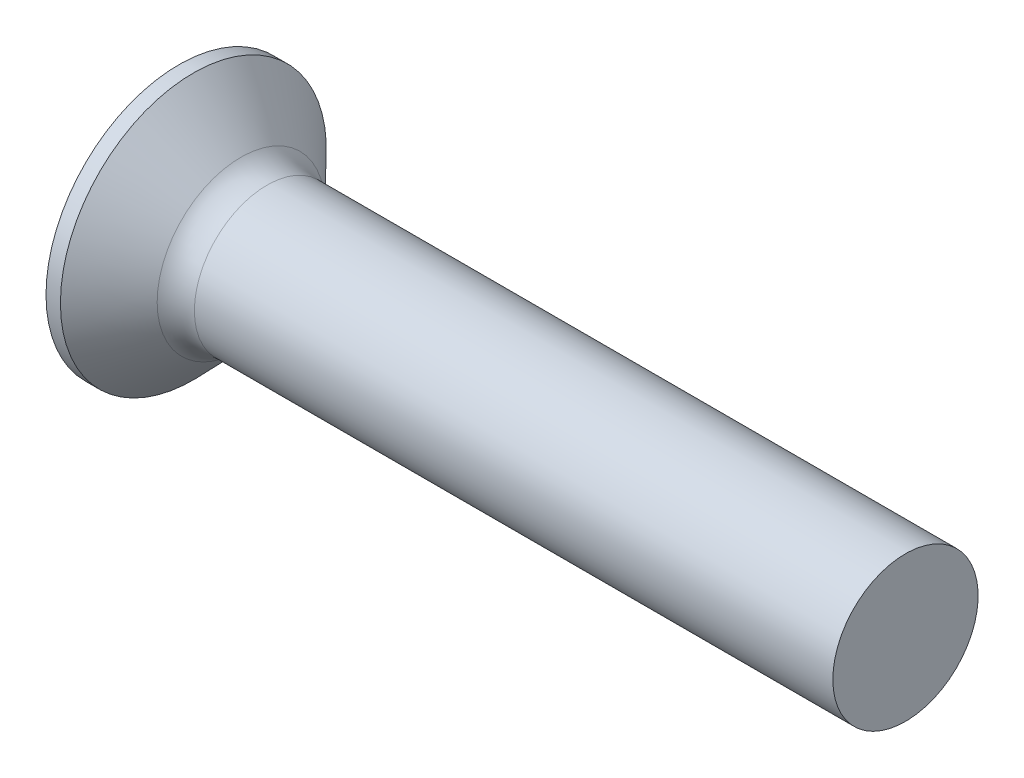
SolidWorks part; units mm, degrees
revolve "Base-Revolve" add sketch "BodySke" angle 360 about L5
sketch "BodySke" plane through (0, 0, 0) normal (0, 0, 1) x (1, 0, 0)
  line L0 (0, 0) -> (0, 9.15)
  line L1 (0, 9.15) -> (0.9924, 9.15)
  line L2 (5, 5) -> (50, 5)
  line L3 (50, 5) -> (50, 0)
  line L4 (50, 0) -> (0, 0)
  line L5 (-6.35, 0) -> (82.55, 0) construction
  line L6 (5, -5) -> (50, -5) construction
  line L7 (0.9924, -9.15) -> (5, -5) construction
  line L8 (0.9924, 9.15) -> (5, 5)
  line L9 (0, -9.15) -> (0.9924, -9.15) construction
  line L10 (6.5, 6.5875) -> (6.5, -2.9375) construction
  line L11 (0, 6.35) -> (0, -3.175) construction
  dimension "Length" = 50
  dimension "Thread_nom" = 50
cosmetic thread "ThreadCosmetic" [suppressed] parameters "Thread_length"=2.85, "Thread_minor"=7.9248
ref_plane "Plane1" through (0, 0, 0) normal (0, 0, 1) x (1, 0, 0)
ref_plane "Plane2" through (0, 0, 0) normal (0, 1, 0) x (1, 0, 0)
ref_plane "Plane3" through (0, 0, 0) normal (1, 0, 0) x (0, 0, -1)
fillet "Fillet1" radius 2.5 1 edges at (5, 0, 5)
sketch "Sketch3" plane through (0, 0, 0) normal (-1, 0, 0) x (0, 0, 1)
  line L0 (-1.08, 4.9) -> (1.08, 4.9)
  line L1 (1.08, 4.9) -> (1.08, -4.9)
  line L2 (1.08, -4.9) -> (-1.08, -4.9)
  line L3 (-1.08, -4.9) -> (-1.08, 4.9)
  dimension "D1" = 1.5
  dimension "D2" = 0.37
ref_plane "Plane4" through (5.64, 0, 0) normal (-1, 0, 0) x (0, 0, 1)
sketch "Sketch4" plane through (5.64, 0, 0) normal (-1, 0, 0) x (0, 0, 1)
  line L0 (-1.08, 2.088) -> (1.08, 2.088)
  line L3 (1.08, 2.088) -> (1.08, -2.088)
  line L4 (1.08, -2.088) -> (-1.08, -2.088)
  line L5 (-1.08, -2.088) -> (-1.08, 2.088)
  dimension "D2" = 0.9957
  dimension "D1" = 0.74
  dimension "D4" = 0.4979
  dimension "D3" = 0.37
loft "Recess" cut profiles "Sketch3", "Sketch4"
pattern_circular "RecPat" count 2 every 90 about axis through (0, 0, 0) along (1, 0, 0) of "Recess"
sketch "RecCorSke" plane through (0, 0, 0) normal (0, 0, 1) x (1, 0, 0)
  line L0 (-3.175, 0) -> (15.875, 0) construction
  line L2 (0, 0) -> (0, 2.3249)
  line L3 (0, 2.3249) -> (5.64, 1.9305)
  line L4 (5.64, 1.9305) -> (6.2673, 0)
  line L5 (6.2673, 0) -> (0, 0)
  dimension "Depth" = 2.01
  dimension "Draft_angle" = 4
  dimension "Bottom_angle" = 18
revolve "RecessCore" cut sketch "RecCorSke" angle 360 about L0
sketch "ThdSchSke" plane through (0, 0, 0) normal (0, 0, 1) x (1, 0, 0)
  line L0 (6.5, -3.9624) -> (5.7735, -5)
  line L1 (6.5, -3.9624) -> (7.2265, -5)
  line L2 (7.2265, -5) -> (7.2265, -6.25)
  line L3 (-3.175, 0) -> (5.1513, 0) construction
  line L5 (7.2265, -6.25) -> (5.7735, -6.25)
  line L6 (5.7735, -6.25) -> (5.7735, -5)
  line L7 (0, 9.15) -> (0, -9.15) construction
  dimension "Thread_minor" = 2.439
  dimension "Diameter" = 3
  dimension "Start" = 2.15
revolve "ThreadSchematic" [suppressed] cut sketch "ThdSchSke" angle 360 about L3
pattern_linear "ThdSchPat" [suppressed]
equation "\"D1@Sketch3\" = \"Cross_dia@Sketch3\" / 2"
equation "\"D2@Sketch3\" = \"Cross_width@Sketch3\" / 2"
equation "\"Depth@RecCorSke\" = \"Cross_depth@Plane4\""
equation "\"D1@Sketch4\" = \"Cross_width@Sketch3\""
equation "\"D2@Sketch4\" = \"Cross_dia@Sketch3\" - 2.0 * \"Cross_depth@Plane4\" * tan(26.5  * 0.017453292)"
equation "\"D3@Sketch4\" = \"D1@Sketch4\" / 2"
equation "\"D4@Sketch4\" = \"D2@Sketch4\" / 2"
equation "\"Thread_length@ThreadCosmetic\" = ((sgn( (\"Length@BodySke\" - \"Advance@BodySke\" * 1.0 - \"Head_ht@BodySke\" ) - \"Thread_nom@BodySke\" )-1)*( (\"Length@BodySke\" - \"Advance@BodySke\" * 1.0 - \"Head_ht@BodySke\" ) - \"Thread_nom@BodySke\" ))/-2+ \"Thread_nom@BodySke\""
equation "\"Thread_minor@ThdSchSke\" = \"Thread_minor@ThreadCosmetic\""
equation "\"Diameter@ThdSchSke\" = \"Diameter@BodySke\""
equation "\"Overcut@ThdSchSke\" = \"Diameter@BodySke\" * 1.25"
equation "\"Start@ThdSchSke\" = 0.000001 + \"Length@BodySke\" - \"Thread_length@ThreadCosmetic\"  '---Countersunk---"
equation "\"Num_threads@ThdSchPat\" = int( \"Thread_length@ThreadCosmetic\" / \"Advance@BodySke\" + 0.999 )  + 1"
equation "\"Advance@ThdSchPat\" = \"Thread_length@ThreadCosmetic\" /  (\"Num_threads@ThdSchPat\" - 1) 'relax it"
